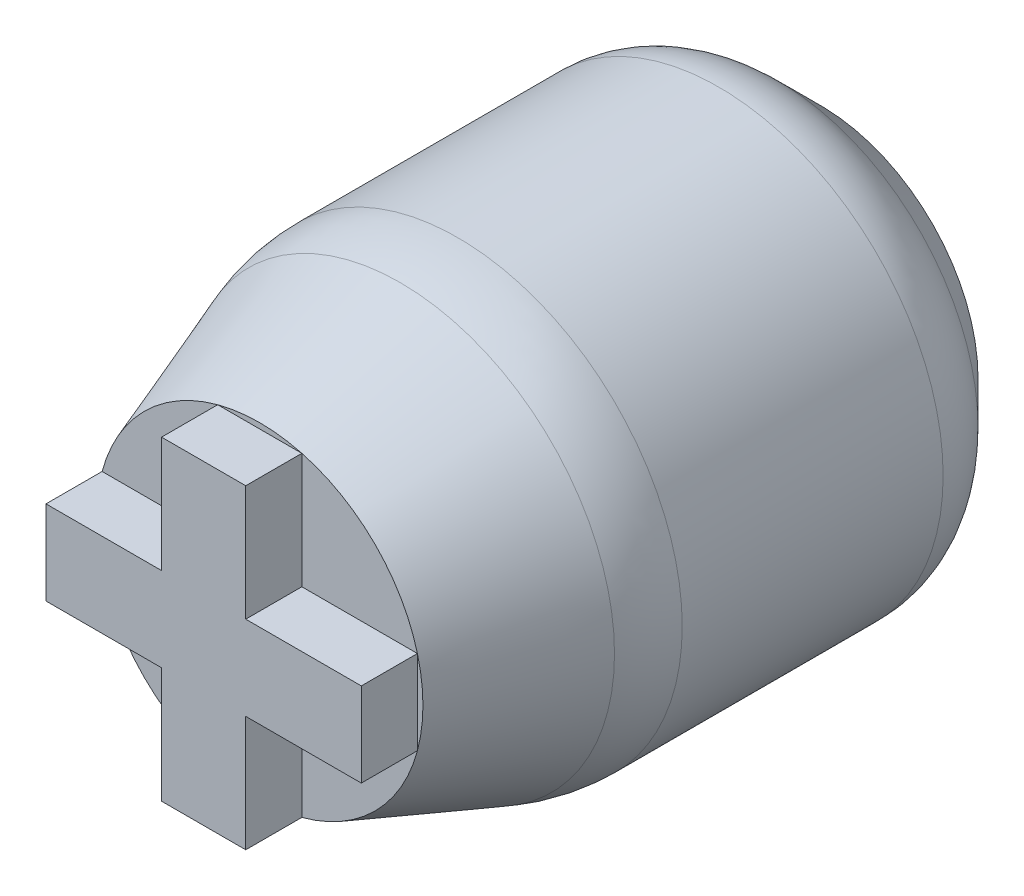
SolidWorks part; units mm, degrees
ref_plane "Ebene vorne" through (0, 0, 0) normal (0, 0, 1) x (1, 0, 0)
ref_plane "Ebene oben" through (0, 0, 0) normal (0, 1, 0) x (1, 0, 0)
ref_plane "Ebene rechts" through (0, 0, 0) normal (1, 0, 0) x (0, 0, -1)
sketch "Sketch1" plane through (0, 0, 0) normal (0, 0, 1) x (1, 0, 0)
  circle A0 centre (0, 0) radius 4
  dimension "D1" = 8
extrude "Boss-Extrude1" add sketch "Sketch1" along normal blind 10
chamfer "Chamfer1" distance 3 angle 20 1 edges at (4, 0, 10)
sketch "Sketch2" plane through (0, 0, 0) normal (0, 0, -1) x (-1, 0, 0)
  line L0 (-1.2329, -0.55) -> (1.2329, -0.55)
  line L1 (0, 1.35) -> (0, -0.4987) construction
  line L2 (0, -0.55) -> (0, -1.0745) construction
  arc A0 (1.2329, -0.55) -> (-1.2329, -0.55) centre (0, 0) ccw
  dimension "D1" = 2.7
  dimension "D2" = 1.9
extrude "Cut-Extrude1" cut sketch "Sketch2" against normal blind 6
chamfer "Chamfer2" distance 1.2 angle 45 1 edges at (4, 0, 0)
fillet "Fillet1" radius 3 1 edges at (4, 0, 7)
fillet "Fillet2" radius 1.5 1 edges at (4, 0, 1.2)
sketch "Sketch3" plane through (0, 0, 10) normal (0, 0, 1) x (1, 0, 0)
  line L0 (-2.8097, 0.75) -> (-0.75, 0.75)
  line L1 (-0.75, 0.75) -> (-0.75, 2.8097)
  line L2 (-0.75, 2.8097) -> (0.75, 2.8097)
  line L3 (0.75, 2.8097) -> (0.75, 0.75)
  line L4 (0.75, 0.75) -> (2.8097, 0.75)
  line L5 (2.8097, 0.75) -> (2.8097, -0.75)
  line L6 (2.8097, -0.75) -> (0.75, -0.75)
  line L7 (0.75, -0.75) -> (0.75, -2.8097)
  line L8 (0.75, -2.8097) -> (-0.75, -2.8097)
  line L9 (-0.75, -2.8097) -> (-0.75, -0.75)
  line L10 (-0.75, -0.75) -> (-2.8097, -0.75)
  line L11 (-2.8097, -0.75) -> (-2.8097, 0.75)
  circle A0 centre (0, 0) radius 2.9081 construction
  dimension "D1" = 1.5
extrude "Boss-Extrude2" add sketch "Sketch3" along normal blind 1
